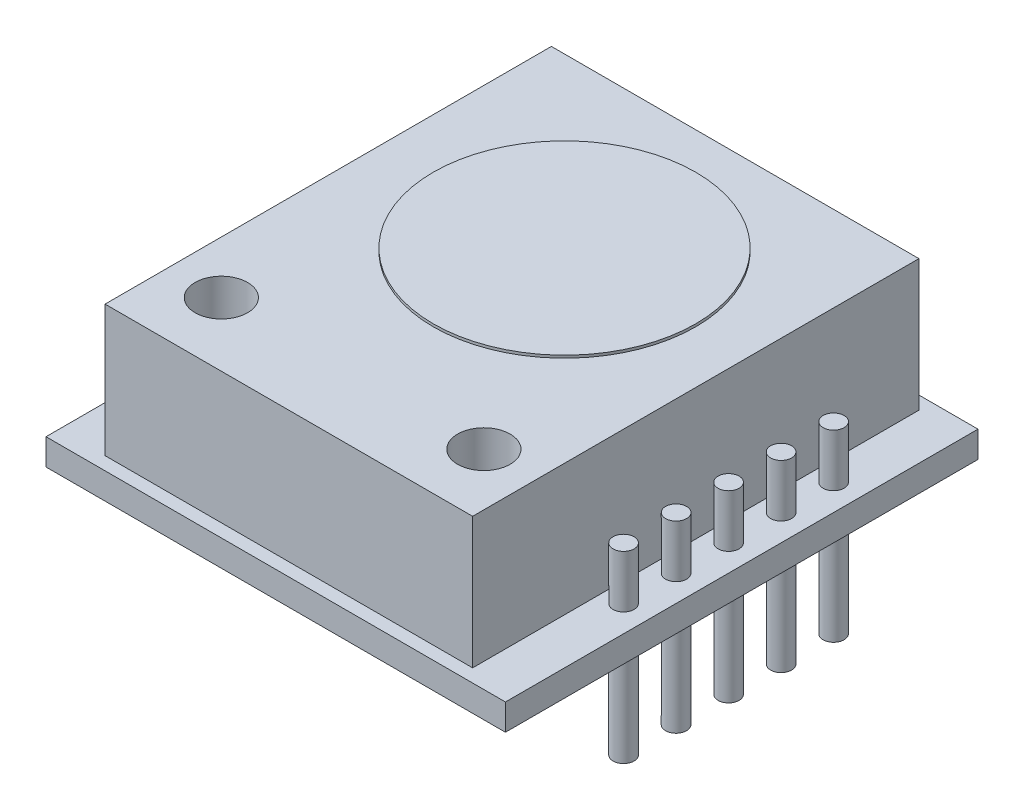
SolidWorks part; units mm, degrees
ref_plane "Спереди" through (0, 0, 0) normal (0, 0, 1) x (1, 0, 0)
ref_plane "Сверху" through (0, 0, 0) normal (0, 1, 0) x (1, 0, 0)
ref_plane "Справа" through (0, 0, 0) normal (1, 0, 0) x (0, 0, -1)
sketch "Sketch1" plane through (0, 0, 0) normal (0, 1, 0) x (1, 0, 0)
  line L1 (-8.75, -9) -> (8.75, -9)
  line L2 (-8.75, -9) -> (-8.75, 9)
  line L3 (-8.75, 9) -> (8.75, 9)
  line L4 (8.75, -9) -> (8.75, 9)
  line L5 (-8.75, -9) -> (8.75, 9) construction
  line L6 (-8.75, 9) -> (8.75, -9) construction
  circle A5 centre (-7.95, -5.1) radius 0.4
  circle A6 centre (-7.95, -3.1) radius 0.4
  circle A7 centre (-7.95, -1.1) radius 0.4
  circle A8 centre (-7.95, 0.9) radius 0.4
  circle A9 centre (-7.95, 2.9) radius 0.4
  circle A10 centre (-7.95, 4.9) radius 0.4
  point P0 (0, 0)
  dimension "D4" = 0.8
  dimension "D3" = 0.8
  dimension "D1" = 17.5
  dimension "D2" = 18
  dimension "D5" = 3.9
  dimension "D6" = 6
extrude "Boss-Extrude1" add sketch "Sketch1" along normal blind 1
sketch "Sketch3" plane through (0, 1, 0) normal (0, 1, 0) x (1, 0, 0)
  line L1 (-7, -8.5) -> (7, -8.5)
  line L2 (-7, -8.5) -> (-7, 8.5)
  line L3 (-7, 8.5) -> (7, 8.5)
  line L4 (7, -8.5) -> (7, 8.5)
  line L5 (-7, -8.5) -> (7, 8.5) construction
  line L6 (-7, 8.5) -> (7, -8.5) construction
  circle A0 centre (-5, -6.0714) radius 1
  circle A1 centre (5, -6.0714) radius 1
  point P0 (0, 0)
  dimension "D5" = 2
  dimension "D6" = 2
  dimension "D1" = 17
  dimension "D2" = 14
  dimension "D3" = 2
  dimension "D4" = 2
extrude "Boss-Extrude2" add sketch "Sketch3" along normal blind 5
sketch "Sketch4" plane through (0, 1, 0) normal (0, 1, 0) x (1, 0, 0)
  line L1 (8.75, 9) -> (-8.75, 9) construction
  circle A0 centre (7.75, 4.5) radius 0.4
  circle A5 centre (7.75, 2.5) radius 0.4
  circle A6 centre (7.75, 0.5) radius 0.4
  circle A7 centre (7.75, -1.5) radius 0.4
  circle A8 centre (7.75, -3.5) radius 0.4
  dimension "D1" = 0.8
  dimension "D2" = 5
  dimension "D3" = 4.5
extrude "Boss-Extrude3" add sketch "Sketch4" along normal blind 2 and the other way blind 5
sketch "Sketch5" plane through (0, 6, 0) normal (0, 1, 0) x (1, 0, 0)
  line L0 (0, 10.0823) -> (0, -10.8877) construction
  line L1 (7, 8.5) -> (-7, 8.5) construction
  circle A0 centre (0, 2) radius 5
  dimension "D1" = 10
  dimension "D2" = 6.5
extrude "Boss-Extrude4" add sketch "Sketch5" along normal blind 0.1
